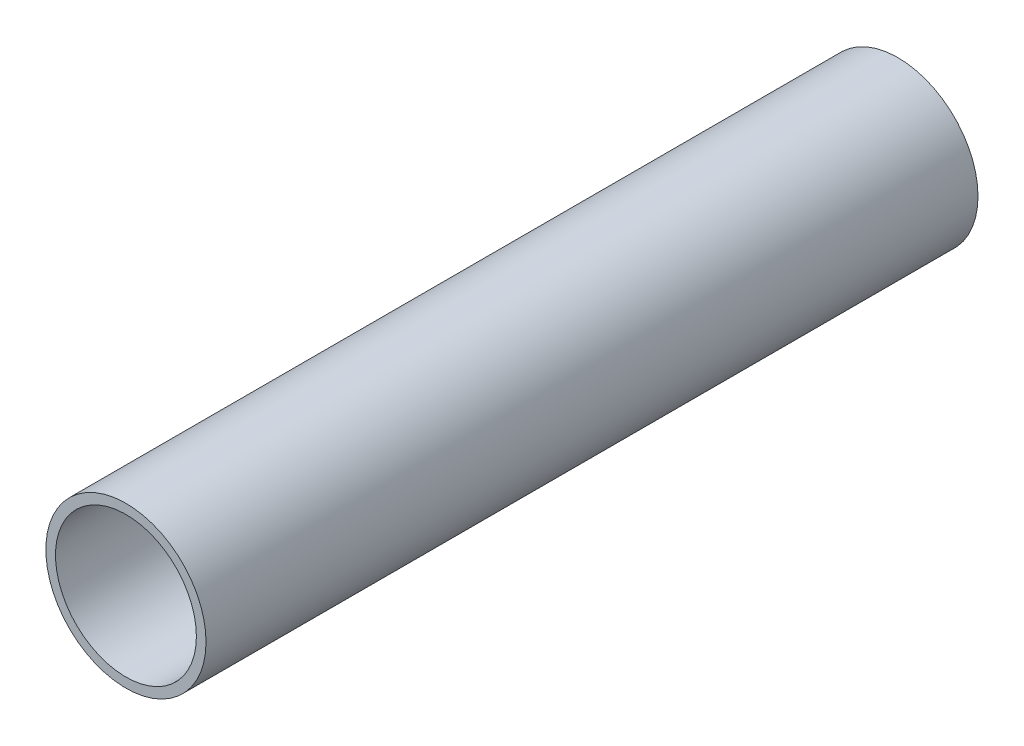
SolidWorks part; units mm, degrees
ref_plane "Front Plane" through (0, 0, 0) normal (0, 0, 1) x (1, 0, 0)
ref_plane "Top Plane" through (0, 0, 0) normal (0, 1, 0) x (1, 0, 0)
ref_plane "Right Plane" through (0, 0, 0) normal (1, 0, 0) x (0, 0, -1)
sketch "Sketch1" plane through (0, 0, 0) normal (0, 0, 1) x (1, 0, 0)
  circle A0 centre (0, 0) radius 41.5
  circle A1 centre (0, 0) radius 36.5
  dimension "D1" = 5
extrude "Boss-Extrude1" add sketch "Sketch1" along normal blind 400
